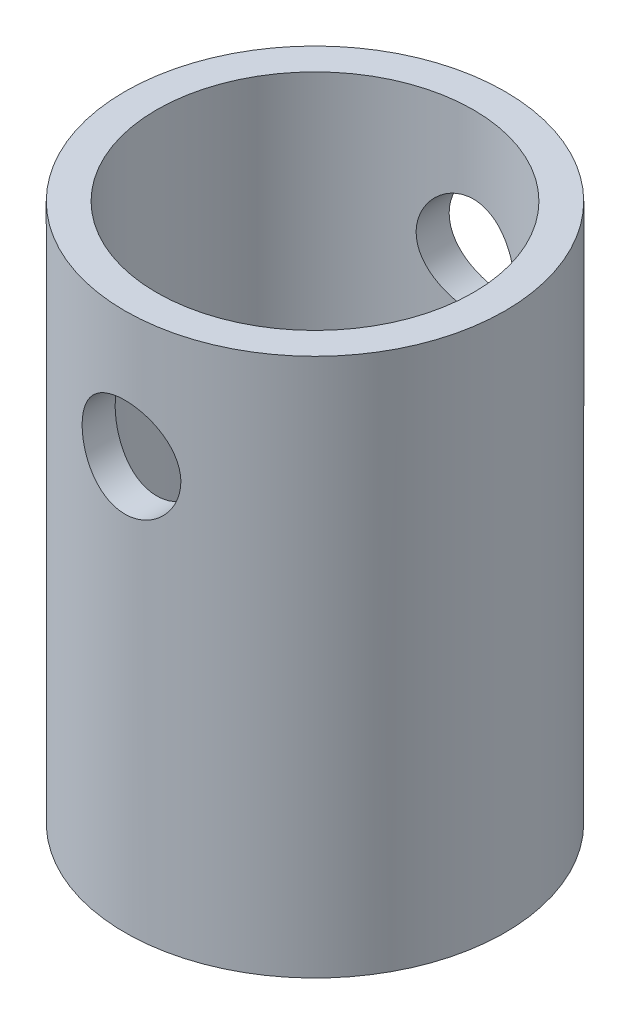
SolidWorks part; units mm, degrees
material "6061 Alloy"
ref_plane "Front Plane" through (0, 0, 0) normal (0, 0, 1) x (1, 0, 0)
ref_plane "Top Plane" through (0, 0, 0) normal (0, 1, 0) x (1, 0, 0)
ref_plane "Right Plane" through (0, 0, 0) normal (1, 0, 0) x (0, 0, -1)
sketch "Sketch1" plane through (0, 0, 0) normal (0, 1, 0) x (1, 0, 0)
  circle A0 centre (0, 0) radius 31.75
  circle A1 centre (0, 0) radius 38.1
  dimension "D1" = 63.5
  dimension "D2" = 6.35
extrude "Boss-Extrude1" add sketch "Sketch1" along normal blind 101.6
sketch "Sketch2" plane through (0, 0, 0) normal (0, -1, 0) x (1, 0, 0)
  circle A0 centre (0, 0) radius 38.1
extrude "Boss-Extrude2" add sketch "Sketch2" along normal blind 6.35
hole_wizard "3/8-24 Tapped Hole1" positions "Sketch6" profile "Sketch3" tap size "3/8-24" standard "ANSI Inch"
sketch "Sketch6" plane through (0, -6.35, 0) normal (0, -1, 0) x (-1, 0, 0)
  circle A0 centre (0, 0) radius 19.05 construction
  point P0 (0, -19.05)
  point P3 (19.05, 0)
  point P5 (0, 19.05)
  point P7 (-19.05, 0)
  dimension "D1" = 38.1
sketch "Sketch3" plane through (0, -6.35, 19.05) normal (1, 0, 0) x (0, 0, -1)
  line L0 (0, 0) -> (0, 24.8855)
  line L1 (0, 24.8855) -> (4.2164, 22.352)
  line L2 (4.2164, 22.352) -> (4.2164, 0)
  line L5 (4.2164, 0) -> (0, 0)
  line L10 (0, 24.8855) -> (-4.2164, 22.352) construction
  line L11 (0, -6.35) -> (0, 107.95) construction
  dimension "Tap Drill Dia." = 8.4328
  dimension "Tap Drill Depth" = 22.352
  dimension "Drill Angle" = 118
cosmetic thread "Hole Thread1" parameters "D1"=6.35, "D2"=9.525
cosmetic thread "Hole Thread2" parameters "D1"=6.35, "D2"=9.525
cosmetic thread "Hole Thread3" parameters "D1"=6.35, "D2"=9.525
cosmetic thread "Hole Thread4" parameters "D1"=6.35, "D2"=9.525
sketch "Sketch8" plane through (0, 0, 0) normal (0, 0, 1) x (1, 0, 0)
  line L0 (31.75, 101.6) -> (-31.75, 101.6) construction
  circle A0 centre (0, 76.2) radius 9.8961
  dimension "D1" = 25.4
extrude "Cut-Extrude1" cut sketch "Sketch8" against normal through all and the other way through all
